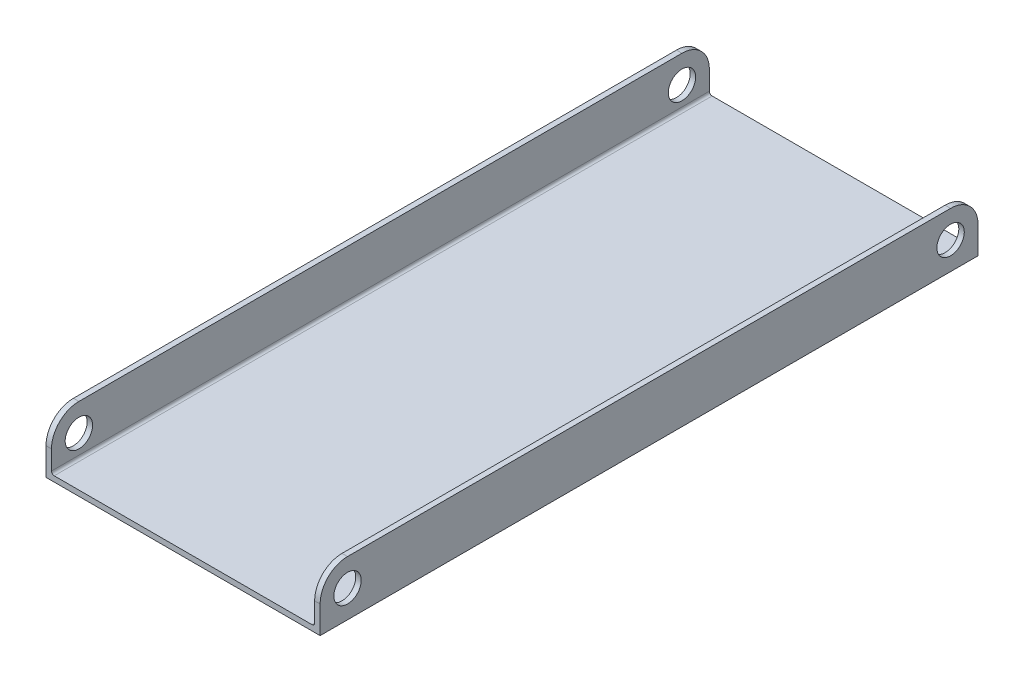
SolidWorks part; units mm, degrees
material "AISI 1020"
ref_plane "Front Plane" through (0, 0, 0) normal (0, 0, 1) x (1, 0, 0)
ref_plane "Top Plane" through (0, 0, 0) normal (0, 1, 0) x (1, 0, 0)
ref_plane "Right Plane" through (0, 0, 0) normal (1, 0, 0) x (0, 0, -1)
sketch "Sketch2" plane through (0, 0, 0) normal (0, 0, 1) x (1, 0, 0)
  line L0 (31.75, 12.7) -> (31.75, 0) construction
  line L1 (0, 0) -> (63.5, 0)
  line L2 (0, 0) -> (0, 12.7)
  line L3 (0, 12.7) -> (63.5, 12.7)
  line L4 (63.5, 0) -> (63.5, 12.7)
  line L6 (1.27, 12.7) -> (62.23, 12.7)
  line L7 (1.27, 12.7) -> (1.27, 1.27)
  line L8 (1.27, 1.27) -> (62.23, 1.27)
  line L9 (62.23, 12.7) -> (62.23, 1.27)
  point P11 (31.75, 1.27)
  dimension "D1" = 63.5
  dimension "D2" = 12.7
  dimension "D3" = 60.96
  dimension "D4" = 11.43
extrude "Boss-Extrude1" add sketch "Sketch2" against normal blind 152.4 contours L0 L8 L7 L3 L2 L1 | L8 L0 L1 L4 L3 L9
fillet "Fillet1" radius 0.635 2 edges at (62.23, 1.27, -76.2) (1.27, 1.27, -76.2)
fillet "Fillet2" radius 6.35 4 edges at (62.865, 12.7, -152.4) (62.865, 12.7, 0) (0.635, 12.7, -152.4) (0.635, 12.7, 0)
sketch "Sketch3" plane through (63.5, 0, 0) normal (1, 0, 0) x (0, 0, -1)
  line L0 (152.4, 0) -> (0, 0) construction
  line L1 (0, 0) -> (0, 6.35) construction
  line L2 (152.4, 0) -> (152.4, 6.35) construction
  circle A0 centre (6.35, 6.35) radius 3.175
  circle A1 centre (146.05, 6.35) radius 3.175
  dimension "D1" = 6.35
  dimension "D2" = 6.35
  dimension "D3" = 6.35
  dimension "D4" = 6.35
extrude "Cut-Extrude1" cut sketch "Sketch3" against normal through all
